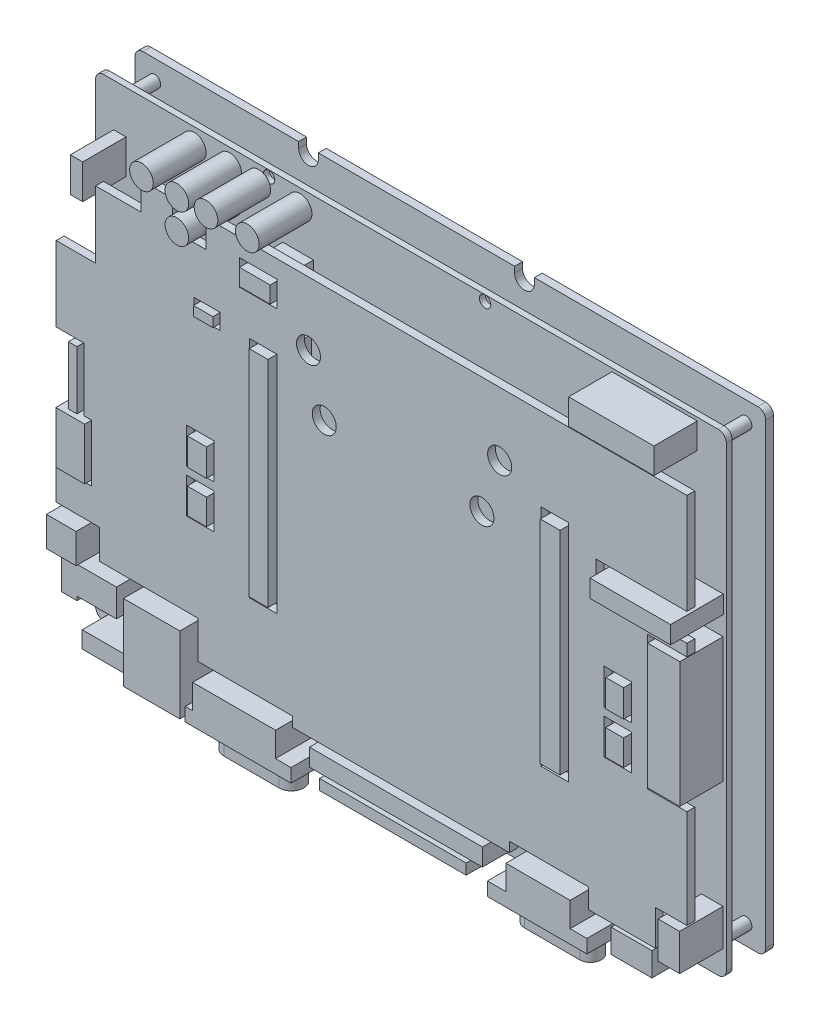
SolidWorks part; units mm, degrees
material "PEI"
ref_plane "前视基准面" through (0, 0, 0) normal (0, 0, 1) x (1, 0, 0)
ref_plane "上视基准面" through (0, 0, 0) normal (0, 1, 0) x (1, 0, 0)
ref_plane "右视基准面" through (0, 0, 0) normal (1, 0, 0) x (0, 0, -1)
other "Configuration Table"
sketch "草图1" plane through (0, 0, 0) normal (0, 0, 1) x (1, 0, 0)
  line L0 (41.5, 118.5) -> (41.5, 120)
  line L1 (0, 0) -> (160, 0)
  line L2 (0, 0) -> (0, 120)
  line L3 (0, 120) -> (160, 120)
  line L4 (160, 0) -> (160, 120)
  line L5 (46.5, 118.5) -> (46.5, 120)
  line L6 (96.3, 118.5) -> (96.3, 120)
  line L7 (101.3, 118.5) -> (101.3, 120)
  circle A0 centre (44, 118.5) radius 2.5
  circle A1 centre (98.8, 118.5) radius 2.5
  dimension "D3" = 5
  dimension "D1" = 120
  dimension "D2" = 160
  dimension "D4" = 118.5
  dimension "D5" = 44
  dimension "D6" = 49.8
extrude "凸台-拉伸1" add sketch "草图1" along normal blind 2 contours A1 L6 L3 L5 A0 L0 L2 L1 L4 L7
fillet "圆角1" radius 2 4 edges at (160, 0, 1) (0, 0, 1) (0, 120, 1) (160, 120, 1)
sketch "草图2" plane through (0, 0, 2) normal (0, 0, 1) x (1, 0, 0)
  line L1 (5, 115) -> (155, 115) construction
  line L2 (5, 115) -> (5, 5) construction
  line L3 (5, 5) -> (155, 5) construction
  line L4 (155, 115) -> (155, 5) construction
  line L8 (0, 2) -> (0, 118) construction
  line L9 (2, 120) -> (41.5, 120) construction
  line L10 (160, 2) -> (160, 118) construction
  line L11 (2, 0) -> (158, 0) construction
  circle A0 centre (5, 115) radius 1.5
  circle A1 centre (5, 5) radius 1.5
  circle A2 centre (155, 5) radius 1.5
  circle A3 centre (155, 115) radius 1.5
  dimension "D5" = 3
  dimension "D6" = 3
  dimension "D7" = 3
  dimension "D8" = 3
  dimension "D1" = 5
  dimension "D2" = 5
  dimension "D3" = 5
  dimension "D4" = 5
extrude "凸台-拉伸2" add sketch "草图2" along normal blind 8.5
sketch "草图3" plane through (0, 0, 10.5) normal (0, 0, 1) x (1, 0, 0)
  line L8 (2, 0) -> (158, 0)
  line L9 (160, 2) -> (160, 118)
  line L10 (158, 120) -> (2, 120)
  line L11 (0, 118) -> (0, 2)
  circle A0 centre (44, 118.5) radius 1.45
  circle A1 centre (98.8, 118.5) radius 1.45
  arc A8 (158, 0) -> (160, 2) centre (158, 2) ccw
  arc A9 (160, 118) -> (158, 120) centre (158, 118) ccw
  arc A10 (2, 120) -> (0, 118) centre (2, 118) ccw
  arc A11 (0, 2) -> (2, 0) centre (2, 2) ccw
  dimension "D1" = 2.9
  dimension "D2" = 2.9
extrude "凸台-拉伸3" add sketch "草图3" along normal blind 1.5
sketch "草图4" plane through (0, 0, 12) normal (0, 0, 1) x (1, 0, 0)
  circle A0 centre (30.044, 79.7034) radius 1.5
  circle A2 centre (25.1617, 17.1058) radius 1.5
  circle A3 centre (139.3718, 12.2236) radius 1.5
  circle A4 centre (139.3718, 104.8122) radius 1.5
  dimension "D1" = 3
  dimension "D2" = 3
  dimension "D3" = 3
  dimension "D4" = 3
extrude "凸台-拉伸4" add sketch "草图4" along normal blind 8
sketch "草图5" plane through (0, 0, 20) normal (0, 0, 1) x (1, 0, 0)
  line L4 (0, 118) -> (0, 2) construction
  line L5 (0, 38) -> (0, 30)
  line L6 (38, 111.5) -> (160, 111.5)
  line L7 (158, 120) -> (2, 120) construction
  line L48 (114.9953, 10.5) -> (114.9953, 13)
  line L49 (160, 2) -> (160, 118) construction
  line L50 (160, 17) -> (160, 42)
  line L51 (0, 30) -> (10.9953, 30)
  line L52 (38, 111.5) -> (38, 104.5)
  line L53 (38, 104.5) -> (29.5, 104.5)
  line L54 (29.5, 104.5) -> (29.5, 111.5)
  line L55 (29.5, 111.5) -> (21.5, 111.5)
  line L56 (21.5, 111.5) -> (21.5, 104.5)
  line L57 (21.5, 104.5) -> (10, 104.5)
  line L58 (10, 104.5) -> (10, 87.5)
  line L59 (10, 87.5) -> (0, 87.5)
  line L60 (0, 87.5) -> (0, 68.5)
  line L61 (0, 68.5) -> (6.9953, 68.5)
  line L62 (6.9953, 68.5) -> (6.9953, 52.5)
  line L63 (6.9953, 52.5) -> (8.9953, 52.5)
  line L64 (8.9953, 52.5) -> (8.9953, 38)
  line L65 (8.9953, 38) -> (0, 38)
  line L66 (10.9953, 30) -> (10.9953, 22.5)
  line L67 (10.9953, 22.5) -> (35.9953, 22.5)
  line L68 (2, 0) -> (158, 0) construction
  line L69 (35.9953, 22.5) -> (35.9953, 13)
  line L70 (35.9953, 13) -> (59.9953, 13)
  line L71 (59.9953, 13) -> (59.9953, 10.5)
  line L72 (59.9953, 10.5) -> (114.9953, 10.5)
  line L73 (114.9953, 13) -> (134.9953, 13)
  line L74 (134.9953, 13) -> (134.9953, 8)
  line L75 (134.9953, 8) -> (151.9953, 8)
  line L76 (151.9953, 8) -> (151.9953, 17)
  line L77 (151.9953, 17) -> (160, 17)
  line L78 (160, 42) -> (150, 42)
  line L79 (150, 42) -> (150, 76)
  line L80 (150, 76) -> (160, 76)
  line L81 (160, 76) -> (160, 79)
  line L82 (160, 79) -> (137, 79)
  line L83 (137, 79) -> (137, 86)
  line L84 (137, 86) -> (160, 86)
  line L85 (160, 86) -> (160, 111.5)
  line L87 (46.5, 107) -> (56, 107)
  line L88 (46.5, 107) -> (46.5, 100.5)
  line L89 (46.5, 100.5) -> (56, 100.5)
  line L90 (56, 107) -> (56, 100.5)
  line L91 (49, 90.5) -> (56, 90.5)
  line L92 (49, 90.5) -> (49, 33.5)
  line L93 (49, 33.5) -> (56, 33.5)
  line L94 (56, 90.5) -> (56, 33.5)
  line L95 (123, 90.5) -> (130, 90.5)
  line L96 (123, 90.5) -> (123, 33.5)
  line L97 (123, 33.5) -> (130, 33.5)
  line L98 (130, 90.5) -> (130, 33.5)
  line L99 (35, 92.5) -> (41.5, 92.5)
  line L100 (35, 92.5) -> (35, 88.5)
  line L101 (35, 88.5) -> (41.5, 88.5)
  line L102 (41.5, 92.5) -> (41.5, 88.5)
  line L103 (33, 63.5) -> (40, 63.5)
  line L104 (33, 63.5) -> (33, 54.5)
  line L105 (33, 54.5) -> (40, 54.5)
  line L106 (40, 63.5) -> (40, 54.5)
  line L107 (33, 52.5) -> (40, 52.5)
  line L108 (33, 52.5) -> (33, 43.5)
  line L109 (33, 43.5) -> (40, 43.5)
  line L110 (40, 52.5) -> (40, 43.5)
  line L111 (139, 63.5) -> (146, 63.5)
  line L112 (139, 63.5) -> (139, 54.5)
  line L113 (139, 54.5) -> (146, 54.5)
  line L114 (146, 63.5) -> (146, 54.5)
  line L115 (139, 52.5) -> (146, 52.5)
  line L116 (139, 52.5) -> (139, 43.5)
  line L117 (139, 43.5) -> (146, 43.5)
  line L118 (146, 52.5) -> (146, 43.5)
  circle A0 centre (112.5, 95.4) radius 3.05
  circle A1 centre (68, 82) radius 3.05
  circle A2 centre (108, 82) radius 3.05
  circle A3 centre (64, 95.4) radius 3.05
  point P86 (41.5, 90.5)
  dimension "D31" = 6.1
  dimension "D2" = 122
  dimension "D1" = 8.5
  dimension "D3" = 8.5
  dimension "D4" = 7
  dimension "D5" = 8
  dimension "D6" = 10
  dimension "D7" = 17
  dimension "D8" = 19
  dimension "D9" = 16
  dimension "D10" = 6.9953
  dimension "D11" = 2
  dimension "D12" = 14.5
  dimension "D13" = 8
  dimension "D14" = 2
  dimension "D15" = 25
  dimension "D16" = 22.5
  dimension "D17" = 13
  dimension "D18" = 24
  dimension "D19" = 2.5
  dimension "D20" = 55
  dimension "D21" = 20
  dimension "D22" = 5
  dimension "D23" = 17
  dimension "D24" = 9
  dimension "D25" = 25
  dimension "D26" = 34
  dimension "D27" = 10
  dimension "D28" = 3
  dimension "D29" = 7
  dimension "D30" = 23
  dimension "D32" = 16.1
  dimension "D33" = 29.5
  dimension "D34" = 48.5
  dimension "D35" = 40
  dimension "D36" = 4
  dimension "D37" = 47.5
  dimension "D38" = 4.5
  dimension "D39" = 6.5
  dimension "D40" = 9.5
  dimension "D41" = 8.5
  dimension "D42" = 10
  dimension "D43" = 57
  dimension "D44" = 7
  dimension "D45" = 67
  dimension "D46" = 9
  dimension "D47" = 2
  dimension "D48" = 7
  dimension "D49" = 9
  dimension "D50" = 10
  dimension "D51" = 9
  dimension "D52" = 6.5
  dimension "D53" = 4
  dimension "D54" = 7.5
extrude "凸台-拉伸5" add sketch "草图5" along normal blind 2
sketch "草图6" plane through (0, 0, 12) normal (0, 0, 1) x (1, 0, 0)
  line L33 (65.2538, 9.3118) -> (109.1308, 9.3118)
  line L34 (65.2538, 9.3118) -> (65.2538, 4.899)
  line L35 (65.2538, 4.899) -> (109.1308, 4.899)
  line L36 (109.1308, 9.3118) -> (109.1308, 4.899)
  line L37 (67.7902, 3.7245) -> (104.9968, 3.7245)
  line L38 (67.7902, 3.7245) -> (67.7902, 1.0501)
  line L39 (67.7902, 1.0501) -> (104.9968, 1.0501)
  line L40 (104.9968, 3.7245) -> (104.9968, 1.0501)
  line L41 (49.9702, 89.2227) -> (54.7063, 89.2227)
  line L42 (49.9702, 89.2227) -> (49.9702, 34.6901)
  line L43 (49.9702, 34.6901) -> (54.7063, 34.6901)
  line L44 (54.7063, 89.2227) -> (54.7063, 34.6901)
  line L45 (123.7961, 88.7213) -> (128.8177, 88.7213)
  line L46 (123.7961, 88.7213) -> (123.7961, 34.9574)
  line L47 (123.7961, 34.9574) -> (128.8177, 34.9574)
  line L48 (128.8177, 88.7213) -> (128.8177, 34.9574)
  line L49 (153.7007, 15.7917) -> (159.1669, 15.7917)
  line L50 (153.7007, 15.7917) -> (153.7007, 6.4995)
  line L51 (153.7007, 6.4995) -> (159.1669, 6.4995)
  line L52 (159.1669, 15.7917) -> (159.1669, 6.4995)
  line L53 (151.0123, 75.0588) -> (159.2012, 75.0588)
  line L54 (151.0123, 75.0588) -> (151.0123, 43.2611)
  line L55 (151.0123, 43.2611) -> (159.2012, 43.2611)
  line L56 (159.2012, 75.0588) -> (159.2012, 43.2611)
  line L57 (131.007, 119.1632) -> (152.6287, 119.1632)
  line L58 (131.007, 119.1632) -> (131.007, 112.6498)
  line L59 (131.007, 112.6498) -> (152.6287, 112.6498)
  line L60 (152.6287, 119.1632) -> (152.6287, 112.6498)
  line L61 (0.888, 51.7584) -> (8.2158, 51.7584)
  line L62 (0.888, 51.7584) -> (0.888, 38.6239)
  line L63 (0.888, 38.6239) -> (8.2158, 38.6239)
  line L64 (8.2158, 51.7584) -> (8.2158, 38.6239)
  line L65 (4.0914, 67.8116) -> (6.2488, 67.8116)
  line L66 (4.0914, 67.8116) -> (4.0914, 53.0274)
  line L67 (4.0914, 53.0274) -> (6.2488, 53.0274)
  line L68 (6.2488, 67.8116) -> (6.2488, 53.0274)
  line L69 (4.583, 109.1226) -> (7.7117, 109.1226)
  line L70 (4.583, 109.1226) -> (4.583, 100.3709)
  line L71 (4.583, 100.3709) -> (7.7117, 100.3709)
  line L72 (7.7117, 109.1226) -> (7.7117, 100.3709)
  line L73 (34.2441, 51.1786) -> (39.1367, 51.1786)
  line L74 (34.2441, 51.1786) -> (34.2441, 44.6552)
  line L75 (34.2441, 44.6552) -> (39.1367, 44.6552)
  line L76 (39.1367, 51.1786) -> (39.1367, 44.6552)
  line L77 (34.2441, 62.2108) -> (39.1367, 62.2108)
  line L78 (34.2441, 62.2108) -> (34.2441, 55.3037)
  line L79 (34.2441, 55.3037) -> (39.1367, 55.3037)
  line L80 (39.1367, 62.2108) -> (39.1367, 55.3037)
  line L81 (35.8296, 91.6425) -> (40.7419, 91.6425)
  line L82 (35.8296, 91.6425) -> (35.8296, 89.2227)
  line L83 (35.8296, 89.2227) -> (40.7419, 89.2227)
  line L84 (40.7419, 91.6425) -> (40.7419, 89.2227)
  line L85 (140.3988, 62.2108) -> (144.9359, 62.2108)
  line L86 (140.3988, 62.2108) -> (140.3988, 55.3037)
  line L87 (140.3988, 55.3037) -> (144.9359, 55.3037)
  line L88 (144.9359, 62.2108) -> (144.9359, 55.3037)
  line L89 (140.3988, 51.1786) -> (144.9359, 51.1786)
  line L90 (140.3988, 51.1786) -> (140.3988, 44.6552)
  line L91 (140.3988, 44.6552) -> (144.9359, 44.6552)
  line L92 (144.9359, 51.1786) -> (144.9359, 44.6552)
  line L93 (47.488, 105.8603) -> (55.2738, 105.8603)
  line L94 (47.488, 105.8603) -> (47.488, 101.636)
  line L95 (47.488, 101.636) -> (55.2738, 101.636)
  line L96 (55.2738, 105.8603) -> (55.2738, 101.636)
extrude "凸台-拉伸6" add sketch "草图6" along normal blind 11
sketch "草图7" plane through (0, 0, 12) normal (0, 0, 1) x (1, 0, 0)
  line L17 (20.4589, 20.788) -> (34.7514, 20.788)
  line L18 (20.4589, 20.788) -> (20.4589, 1.4634)
  line L19 (20.4589, 1.4634) -> (34.7514, 1.4634)
  line L20 (34.7514, 20.788) -> (34.7514, 1.4634)
  line L21 (38.0007, 11.1257) -> (59.0355, 11.1257)
  line L22 (38.0007, 11.1257) -> (38.0007, 4.8837)
  line L23 (38.0007, 4.8837) -> (59.0355, 4.8837)
  line L24 (59.0355, 11.1257) -> (59.0355, 4.8837)
  line L25 (36.1195, 4.8837) -> (62.9688, 4.8837)
  line L26 (36.1195, 4.8837) -> (36.1195, 1.4634)
  line L27 (36.1195, 1.4634) -> (62.9688, 1.4634)
  line L28 (62.9688, 4.8837) -> (62.9688, 1.4634)
  line L29 (117.4831, 11.1257) -> (133.7695, 11.1257)
  line L30 (117.4831, 11.1257) -> (117.4831, 4.8837)
  line L31 (117.4831, 4.8837) -> (133.7695, 4.8837)
  line L32 (133.7695, 11.1257) -> (133.7695, 4.8837)
  line L33 (112.8008, 4.8837) -> (138.0446, 4.8837)
  line L34 (112.8008, 4.8837) -> (112.8008, 1.4634)
  line L35 (112.8008, 1.4634) -> (138.0446, 1.4634)
  line L36 (138.0446, 4.8837) -> (138.0446, 1.4634)
  line L41 (138.8145, 84.4443) -> (159.2564, 84.4443)
  line L42 (138.8145, 84.4443) -> (138.8145, 79.9756)
  line L43 (138.8145, 79.9756) -> (159.2564, 79.9756)
  line L44 (159.2564, 84.4443) -> (159.2564, 79.9756)
  line L45 (0.9087, 29.489) -> (8.4389, 29.489)
  line L46 (0.9087, 29.489) -> (0.9087, 21.9587)
  line L47 (0.9087, 21.9587) -> (8.4389, 21.9587)
  line L48 (8.4389, 29.489) -> (8.4389, 21.9587)
  circle A7 centre (34.0093, 108.2104) radius 3
  circle A8 centre (25.0266, 115.7691) radius 3
  circle A9 centre (34.0093, 115.7691) radius 3
  circle A10 centre (41.4, 115.7691) radius 3
  circle A11 centre (51.87, 115.7691) radius 3
  dimension "D1" = 6
extrude "凸台-拉伸7" add sketch "草图7" along normal blind 13.4 contours L48 L45 L46 L47 | L20 L17 L18 L19 | L24 L21 L22 L23 | A8 | A9 | A10 | A11 | A7 | L44 L41 L42 L43 | L36 L33 L31 L34 L35 | L28 L25 L23 L26 L27 | L32 L29 L30 L31
sketch "草图8" plane through (0, 0, 12) normal (0, 0, 1) x (1, 0, 0)
  line L0 (2, 0) -> (158, 0) construction
  line L1 (1.2771, 20) -> (5.2771, 20)
  line L2 (1.2771, 20) -> (1.2771, 11)
  line L3 (1.2771, 11) -> (5.2771, 11)
  line L4 (5.2771, 20) -> (5.2771, 11)
  line L5 (5.2771, 19) -> (15.2771, 19)
  line L6 (5.2771, 19) -> (5.2771, 12)
  line L7 (5.2771, 12) -> (15.2771, 12)
  line L8 (15.2771, 19) -> (15.2771, 12)
  line L9 (6.5807, 5.2697) -> (18.8367, 5.2697)
  line L10 (6.5807, 5.2697) -> (6.5807, 1.0272)
  line L11 (6.5807, 1.0272) -> (18.8367, 1.0272)
  line L12 (18.8367, 5.2697) -> (18.8367, 1.0272)
  line L13 (140.8021, 7.039) -> (151.1272, 7.039)
  line L14 (140.8021, 7.039) -> (140.8021, 1.0272)
  line L15 (140.8021, 1.0272) -> (151.1272, 1.0272)
  line L16 (151.1272, 7.039) -> (151.1272, 1.0272)
  point P18 (15.2771, 15.5)
  point P19 (5.2771, 15.5)
  dimension "D1" = 11
  dimension "D2" = 9
  dimension "D3" = 4
  dimension "D4" = 10
  dimension "D5" = 7
extrude "凸台-拉伸8" add sketch "草图8" along normal blind 10 contours L8 L5 L4 L7 | L4 L1 L2 L3 | L16 L13 L14 L15 | L12 L9 L10 L11
sketch "草图9" plane through (1.2771, 0, 0) normal (-1, 0, 0) x (0, 0, 1)
  line L0 (22, 20) -> (22, 11) construction
  line L1 (10.5, 118) -> (10.5, 2) construction
  circle A0 centre (18.5, 15.5) radius 3
  point P5 (22, 15.5)
  dimension "D1" = 6
  dimension "D2" = 8
extrude "切除-拉伸1" cut sketch "草图9" against normal blind 9.5
sketch "草图11" plane through (0, 1.4634, 0) normal (0, -1, 0) x (1, 0, 0)
  line L0 (42.5442, 18.8709) -> (56.5442, 18.8709) construction
  line L1 (42.5442, 21.9812) -> (56.5442, 21.9812)
  line L2 (42.5442, 15.7605) -> (56.5442, 15.7605)
  line L3 (118.4227, 18.8709) -> (132.4227, 18.8709) construction
  line L4 (118.4227, 21.6007) -> (132.4227, 21.6007)
  line L5 (118.4227, 16.1411) -> (132.4227, 16.1411)
  line L6 (36.1195, 25.4) -> (62.9688, 25.4) construction
  line L7 (112.8008, 25.4) -> (138.0446, 25.4) construction
  arc A0 (42.5442, 21.9812) -> (42.5442, 15.7605) centre (42.5442, 18.8709) ccw
  arc A1 (56.5442, 15.7605) -> (56.5442, 21.9812) centre (56.5442, 18.8709) ccw
  arc A2 (118.4227, 21.6007) -> (118.4227, 16.1411) centre (118.4227, 18.8709) ccw
  arc A3 (132.4227, 16.1411) -> (132.4227, 21.6007) centre (132.4227, 18.8709) ccw
  point P2 (49.5442, 18.8709)
  point P7 (125.4227, 18.8709)
  point P17 (49.5442, 25.4)
  point P20 (125.4227, 25.4)
  dimension "D1" = 14
  dimension "D2" = 14
extrude "凸台-拉伸9" add sketch "草图11" along normal blind 6
